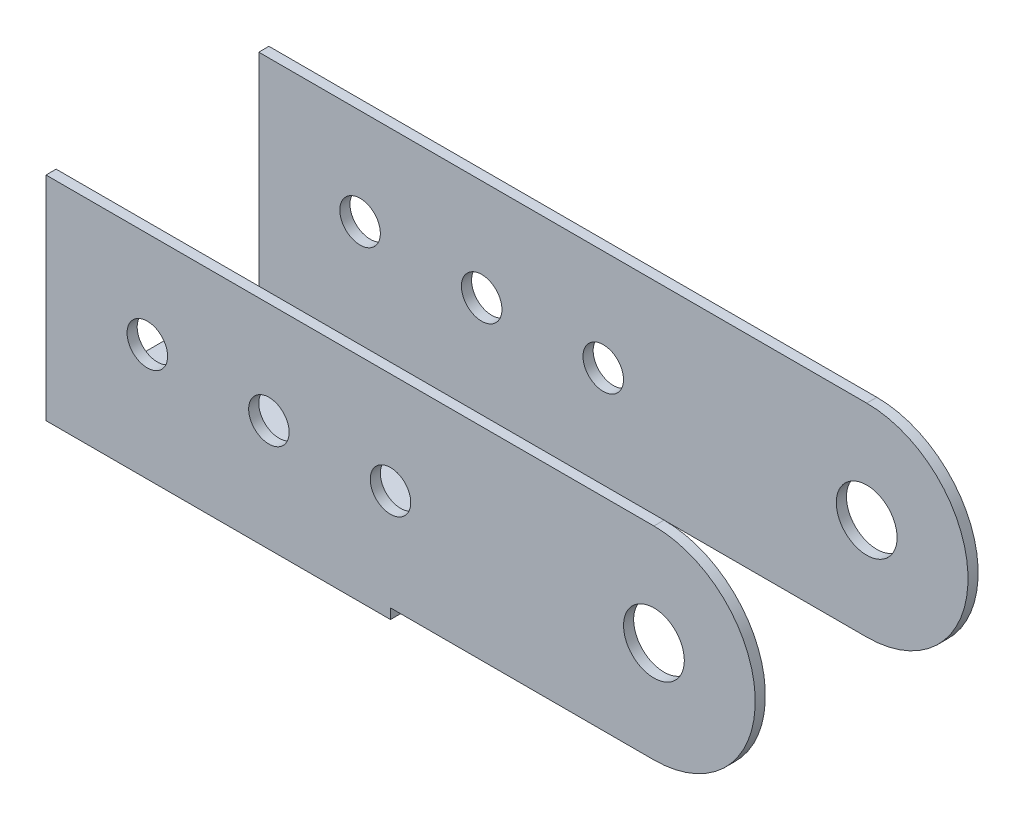
SolidWorks part; units mm, degrees
ref_plane "前视" through (0, 0, 0) normal (0, 0, 1) x (1, 0, 0)
ref_plane "上视" through (0, 0, 0) normal (0, 1, 0) x (1, 0, 0)
ref_plane "右视" through (0, 0, 0) normal (1, 0, 0) x (0, 0, -1)
sketch "草图1" plane through (0, 0, 0) normal (0, 0, 1) x (1, 0, 0)
  line L0 (-10, 13.6585) -> (-10, -13.1517) construction
  line L1 (-15, 5) -> (15, 5)
  line L2 (-15, 5) -> (-15, -5)
  line L3 (-15, -5) -> (15, -5)
  line L4 (-16.7978, 0) -> (28.1127, 0) construction
  line L7 (-4, 13.6585) -> (-4, -13.1517) construction
  line L8 (2, 13.6585) -> (2, -13.1517) construction
  arc A0 (15, -5) -> (15, 5) centre (15, 0) ccw
  circle A1 centre (15, 0) radius 1.5
  circle A2 centre (-10, 0.2534) radius 1
  circle A3 centre (-4, 0) radius 1
  circle A4 centre (2, 0) radius 1
  point P0 (0, 0)
  dimension "D3" = 10
  dimension "D4" = 3
  dimension "D8" = 2
  dimension "D9" = 2
  dimension "D10" = 2
  dimension "D1" = 10
  dimension "D2" = 30
  dimension "D5" = 5
  dimension "D6" = 11
  dimension "D7" = 17
ref_plane "基准面1" through (0, 0, 10) normal (0, 0, 1) x (1, 0, 0)
sketch "草图2" plane through (0, 0, 10) normal (0, 0, 1) x (1, 0, 0)
  line L3 (15, 5) -> (-15, 5)
  line L4 (-15, -5) -> (15, -5)
  line L5 (-15, 5) -> (-15, -5)
  line L6 (15, 5) -> (-15, 5)
  line L7 (-15, -5) -> (15, -5)
  line L8 (-15, 5) -> (-15, -5)
  circle A1 centre (15, 0) radius 1.5
  circle A2 centre (15, 0) radius 1.5
  arc A3 (15, -5) -> (15, 5) centre (15, 0) ccw
  arc A4 (15, -5) -> (15, 5) centre (15, 0) ccw
  circle A5 centre (2, 0) radius 1
  circle A6 centre (2, 0) radius 1
  circle A7 centre (-4, 0) radius 1
  circle A8 centre (-4, 0) radius 1
  circle A9 centre (-10, 0.2534) radius 1
  circle A10 centre (-10, 0.2534) radius 1
  dimension "D1" = 0
  dimension "D2" = 0
  dimension "D3" = 0
  dimension "D4" = 0
  dimension "D5" = 0
extrude "凸台-拉伸1" add sketch "草图2" along normal blind 0.5
extrude "凸台-拉伸2" add sketch "草图1" against normal blind 0.5 separate body
ref_plane "基准面2" through (0, -5, 0) normal (0, -1, 0) x (-1, 0, 0)
sketch "草图3" plane through (0, -5, 0) normal (0, -1, 0) x (-1, 0, 0)
  line L0 (-2, 0.5) -> (15, 0.5)
  line L1 (-2, 0.5) -> (-2, 0) construction
  line L2 (15, 0.5) -> (-15, 0.5) construction
  line L3 (15, 0.5) -> (15, -10.5)
  line L4 (15, -10.5) -> (-2, -10.5)
  line L5 (-2, -10.5) -> (-2, -10) construction
  line L6 (15, -10.5) -> (-15, -10.5) construction
  line L7 (-2, -10.5) -> (-2, 0.5)
extrude "凸台-拉伸3" add sketch "草图3" along normal blind 0.5
